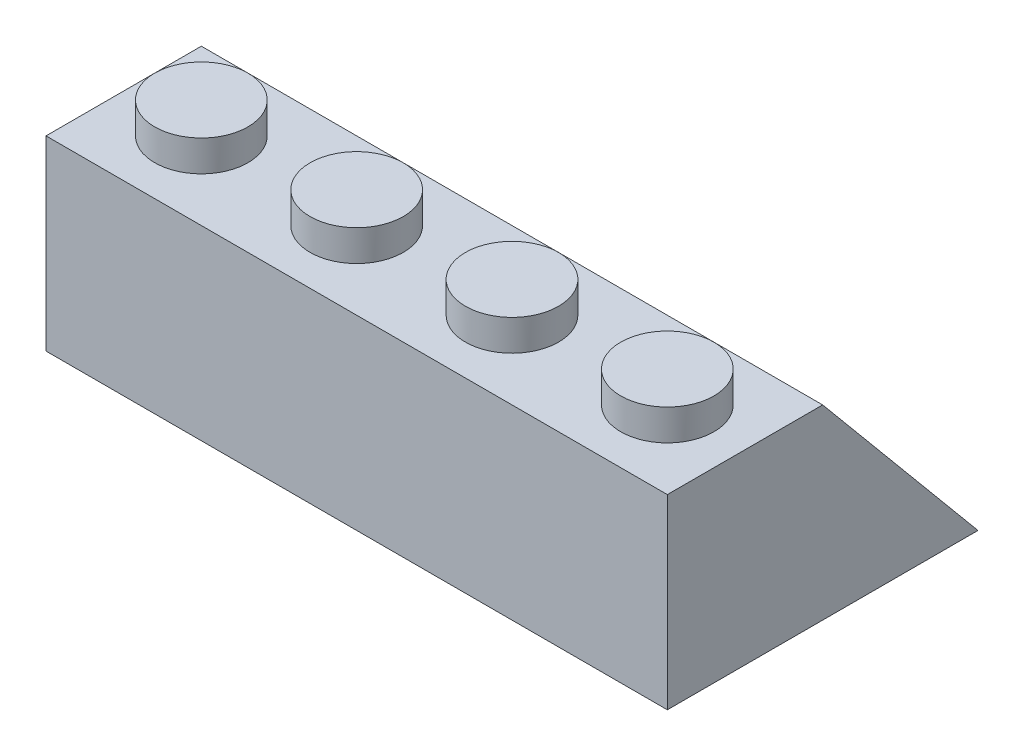
SolidWorks part; units mm, degrees
ref_plane "Front Plane" through (0, 0, 0) normal (0, 0, 1) x (1, 0, 0)
ref_plane "Top Plane" through (0, 0, 0) normal (0, 1, 0) x (1, 0, 0)
ref_plane "Right Plane" through (0, 0, 0) normal (1, 0, 0) x (0, 0, -1)
sketch "Sketch1" plane through (0, 0, 0) normal (1, 0, 0) x (0, 0, -1)
  line L0 (0, 0) -> (16, 0)
  line L2 (8, 9.6) -> (0, 9.6)
  line L3 (0, 9.6) -> (0, 0)
  line L6 (8, 9.6) -> (16, 0)
  dimension "D1" = 9.6
  dimension "D2" = 8
  dimension "D3" = 16
extrude "Boss-Extrude1" add sketch "Sketch1" along normal blind 32
sketch "Sketch2" plane through (0, 9.6, 0) normal (0, 1, 0) x (1, 0, 0)
  line L0 (0, 4) -> (4, 4) construction
  line L1 (0, 8) -> (0, 0) construction
  circle A0 centre (4, 4) radius 2.4
  dimension "D2" = 4.8
  dimension "D1" = 4
extrude "Boss-Extrude2" add sketch "Sketch2" along normal blind 1.6
pattern_linear "LPattern1" count 4 spacing 8 along (1, 0, 0) of "Boss-Extrude2"
shell "Shell1" thickness 1.6
